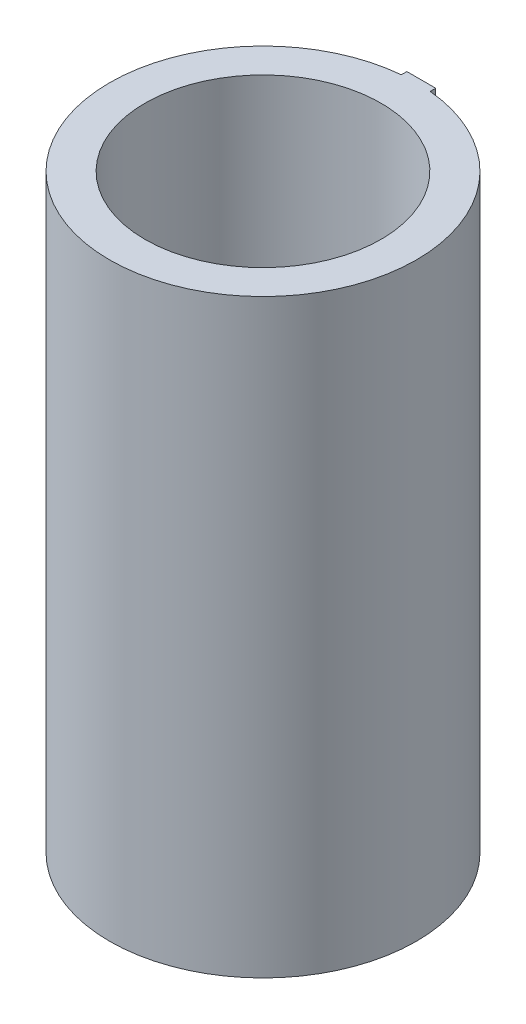
SolidWorks part; units mm, degrees
ref_plane "Alzado" through (0, 0, 0) normal (0, 0, 1) x (1, 0, 0)
ref_plane "Planta" through (0, 0, 0) normal (0, 1, 0) x (1, 0, 0)
ref_plane "Vista lateral" through (0, 0, 0) normal (1, 0, 0) x (0, 0, -1)
sketch "Croquis1" plane through (0, 0, 0) normal (0, 1, 0) x (1, 0, 0)
  circle A0 centre (0, 0) radius 13
  circle A1 centre (0, 0) radius 10
  dimension "D1" = 26
  dimension "D2" = 20
extrude "Saliente-Extruir1" add sketch "Croquis1" along normal blind 50
sketch "Croquis2" plane through (0, 50, 0) normal (0, 1, 0) x (1, 0, 0)
  line L1 (-1.2222, 13.4117) -> (1.2222, 13.4117)
  line L2 (-1.2222, 13.4117) -> (-1.2222, 12.5883)
  line L3 (-1.2222, 12.5883) -> (1.2222, 12.5883)
  line L4 (1.2222, 13.4117) -> (1.2222, 12.5883)
  line L5 (-1.2222, 13.4117) -> (1.2222, 12.5883) construction
  line L6 (-1.2222, 12.5883) -> (1.2222, 13.4117) construction
  circle A0 centre (0, 0) radius 13 construction
  point P0 (0, 13)
extrude "Saliente-Extruir2" add sketch "Croquis2" against normal up to surface (50 mm away) up to face at (0, 0, 13)
